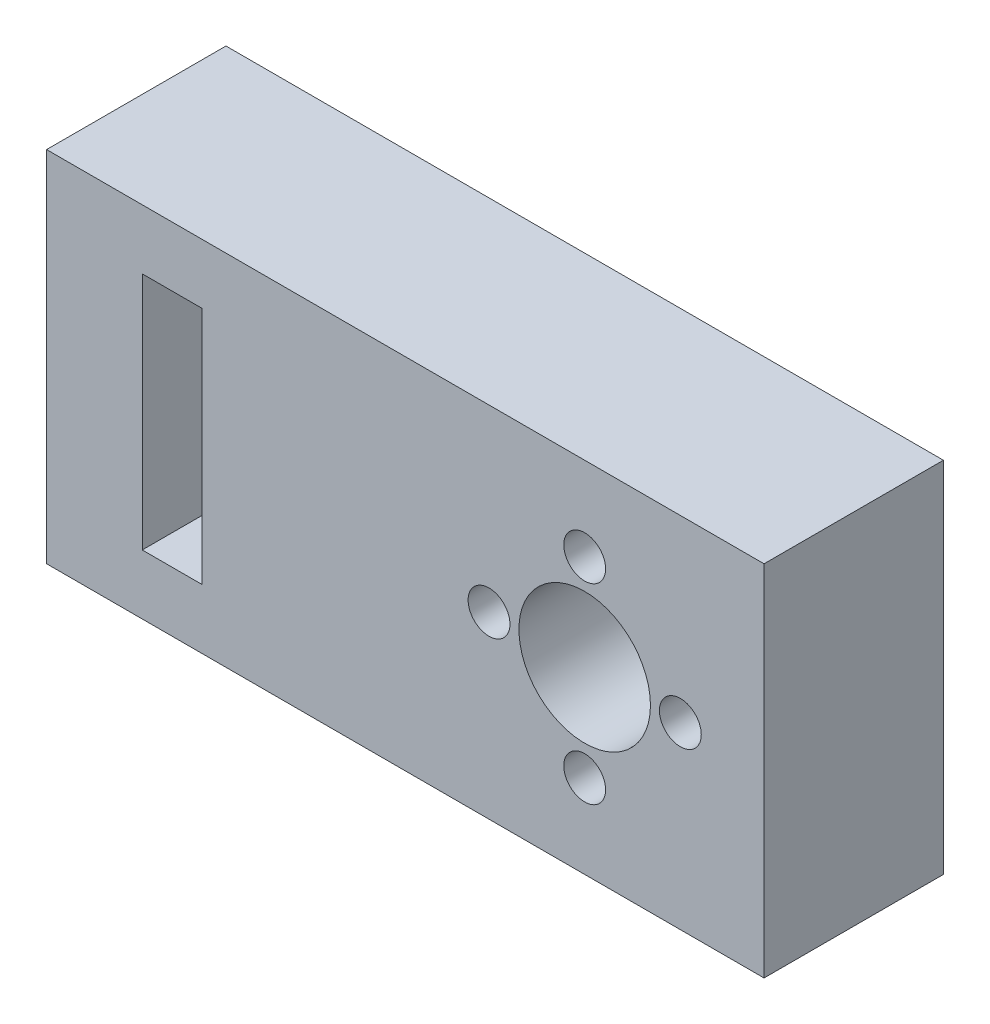
SolidWorks part; units mm, degrees
ref_plane "Front Plane" through (0, 0, 0) normal (0, 0, 1) x (1, 0, 0)
ref_plane "Top Plane" through (0, 0, 0) normal (0, 1, 0) x (1, 0, 0)
ref_plane "Right Plane" through (0, 0, 0) normal (1, 0, 0) x (0, 0, -1)
sketch "Sketch1" plane through (0, 0, 0) normal (0, 0, 1) x (1, 0, 0)
  line L1 (-30, 15) -> (30, 15)
  line L2 (-30, 15) -> (-30, -15)
  line L3 (-30, -15) -> (30, -15)
  line L4 (30, 15) -> (30, -15)
  line L5 (-30, 15) -> (30, -15) construction
  line L6 (-30, -15) -> (30, 15) construction
  line L7 (-22, 10) -> (-17, 10)
  line L8 (-22, 10) -> (-22, -10)
  line L9 (-22, -10) -> (-17, -10)
  line L10 (-17, 10) -> (-17, -10)
  circle A0 centre (15, 0) radius 5.5
  circle A1 centre (15, 8) radius 1.75
  circle A2 centre (23, 0) radius 1.75
  circle A3 centre (15, -8) radius 1.75
  circle A4 centre (7, 0) radius 1.75
  point P0 (0, 0)
  point P24 (15, 0)
  dimension "D1" = 11
  dimension "D9" = 3.5
  dimension "D2" = 45
  dimension "D3" = 60
  dimension "D4" = 30
  dimension "D5" = 8
  dimension "D6" = 5
  dimension "D7" = 20
  dimension "D8" = 5
  dimension "D10" = 8
  dimension "D11" = 4
extrude "Boss-Extrude1" add sketch "Sketch1" along normal mid plane 15
sketch "Sketch2" plane through (-30, 0, 0) normal (-1, 0, 0) x (0, 0, 1)
  circle A0 centre (0, 0) radius 2.5
  dimension "D1" = 5
extrude "Cut-Extrude1" cut sketch "Sketch2" against normal up to surface (8 mm away) up to face at (-22, 0, 0)
